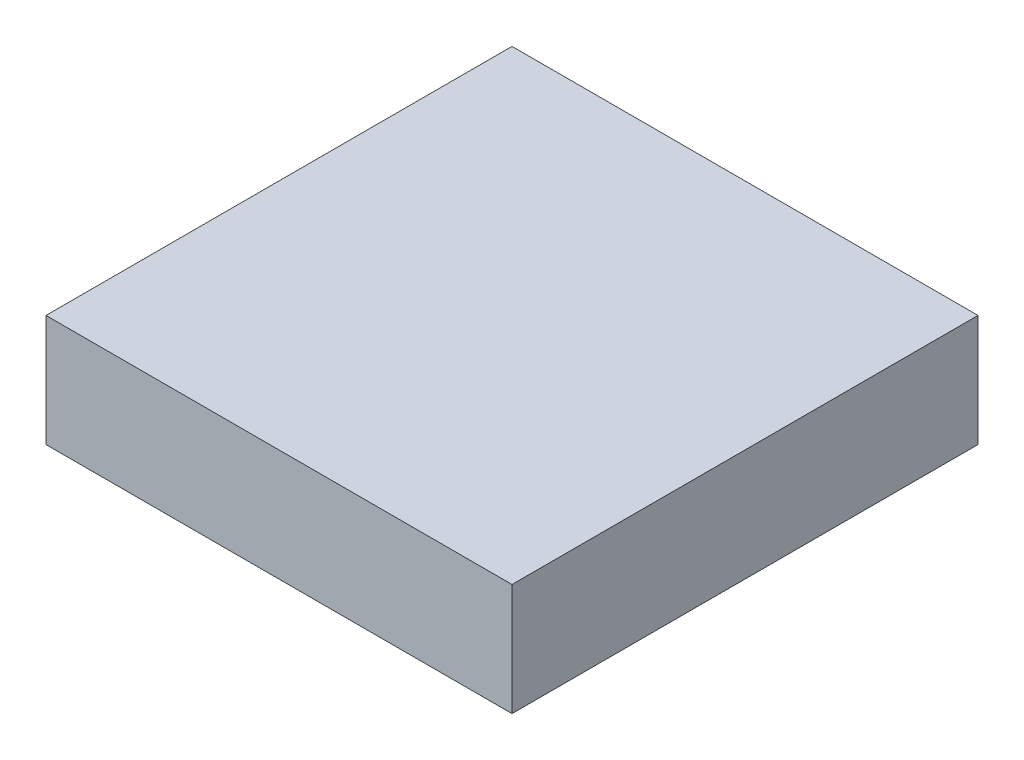
SolidWorks part; units mm, degrees
ref_plane "Plane1" through (0, 0, 0) normal (0, 0, 1) x (1, 0, 0)
ref_plane "Plane2" through (0, 0, 0) normal (0, 1, 0) x (1, 0, 0)
ref_plane "Plane3" through (0, 0, 0) normal (1, 0, 0) x (0, 0, -1)
other "Configuration Table"
sketch "Sketch1" plane through (0, 0, 0) normal (0, 0, 1) x (1, 0, 0)
  line L1 (0, 0) -> (50, 0)
  line L2 (0, 0) -> (0, 12)
  line L3 (0, 12) -> (50, 12)
  line L4 (50, 0) -> (50, 12)
  dimension "D1" = 12
  dimension "D2" = 50
extrude "Base-Extrude" add sketch "Sketch1" against normal blind 50
